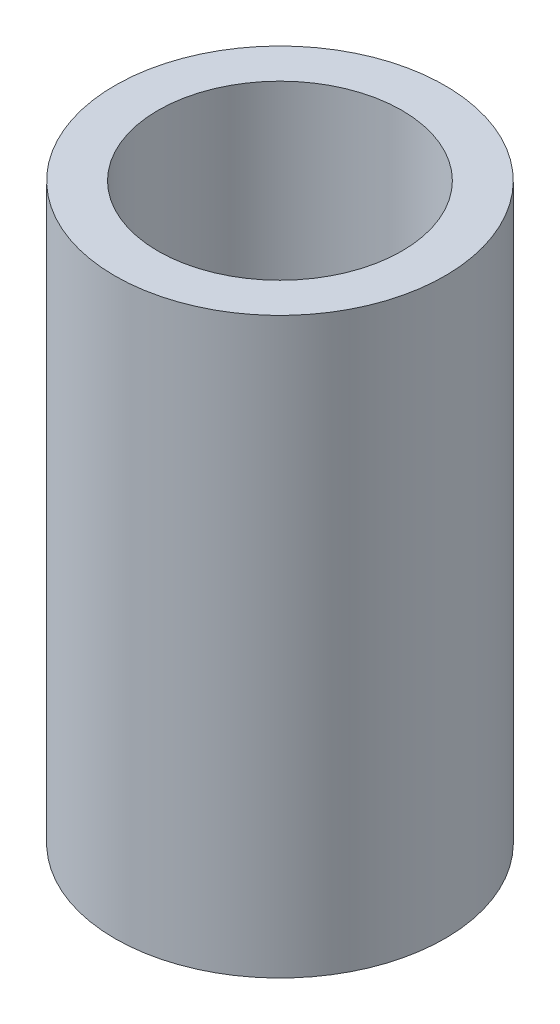
SolidWorks part; units mm, degrees
ref_plane "Front Plane" through (0, 0, 0) normal (0, 0, 1) x (1, 0, 0)
ref_plane "Top Plane" through (0, 0, 0) normal (0, 1, 0) x (1, 0, 0)
ref_plane "Right Plane" through (0, 0, 0) normal (1, 0, 0) x (0, 0, -1)
sketch "Sketch1" plane through (0, 0, 0) normal (0, 1, 0) x (1, 0, 0)
  circle A0 centre (0, 0) radius 4.25
  circle A1 centre (0, 0) radius 5.75
  dimension "D1" = 8.5
  dimension "D2" = 11.5
extrude "Boss-Extrude1" add sketch "Sketch1" along normal blind 20
